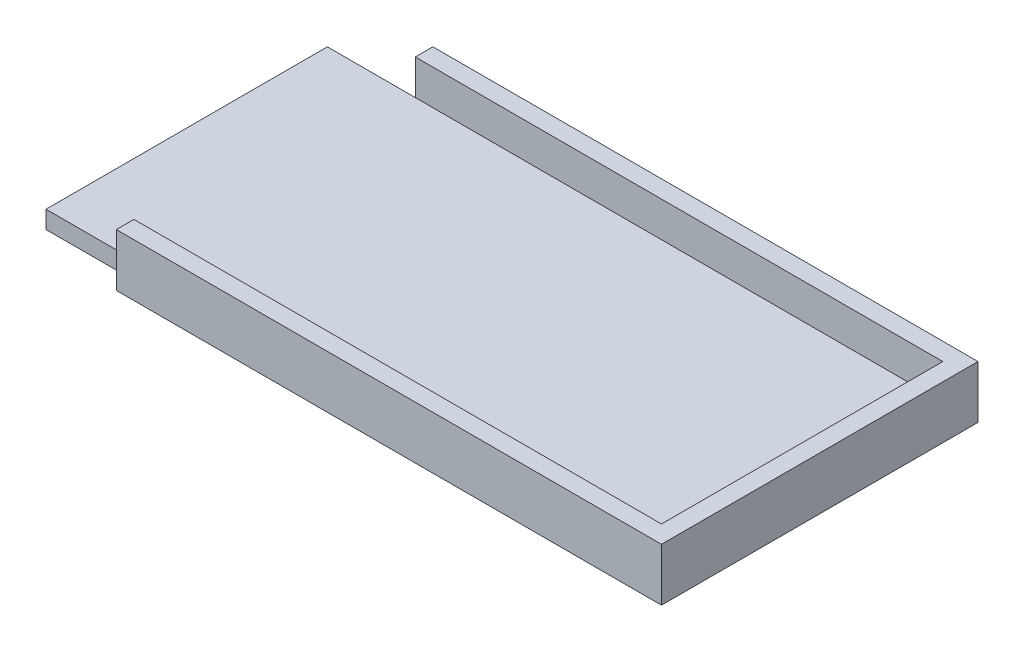
SolidWorks part; units mm, degrees
ref_plane "Front Plane" through (0, 0, 0) normal (0, 0, 1) x (1, 0, 0)
ref_plane "Top Plane" through (0, 0, 0) normal (0, 1, 0) x (1, 0, 0)
ref_plane "Right Plane" through (0, 0, 0) normal (1, 0, 0) x (0, 0, -1)
sketch "Sketch1" plane through (0, 0, 0) normal (0, 1, 0) x (1, 0, 0)
  line L1 (30, -16) -> (-30, -16)
  line L2 (30, -16) -> (30, 16)
  line L3 (30, 16) -> (-30, 16)
  line L4 (-30, -16) -> (-30, 16)
  line L5 (30, -16) -> (-30, 16) construction
  line L6 (30, 16) -> (-30, -16) construction
  point P0 (0, 0)
  dimension "D1" = 60
  dimension "D2" = 32
extrude "Boss-Extrude1" add sketch "Sketch1" along normal blind 2
sketch "Sketch2" plane through (0, 0, 0) normal (0, -1, 0) x (1, 0, 0)
  line L1 (-30, -18) -> (32, -18)
  line L2 (32, -18) -> (32, 18)
  line L3 (32, 18) -> (-30, 18)
  line L4 (-30, 16) -> (-30, -16)
  line L5 (-30, -16) -> (30, -16)
  line L6 (30, -16) -> (30, 16)
  line L7 (30, 16) -> (-30, 16)
  line L9 (-30, -16) -> (30, -16)
  line L10 (30, -16) -> (30, 16)
  line L11 (30, 16) -> (-30, 16)
  line L12 (-32, 18) -> (-32, -18) construction
  line L13 (-30, 16) -> (-30, -16) construction
  line L14 (-30, 16) -> (-30, 18)
  line L15 (-30, -16) -> (-30, -18)
  line L17 (32, 18) -> (-32, 18) construction
  line L18 (-32, -18) -> (32, -18) construction
  dimension "D1" = 0
  dimension "D2" = 2
extrude "Boss-Extrude2" add sketch "Sketch2" along direction (0, -1, 0) on the side against the normal offset from surface (6 mm away) 4
sketch "Sketch3" plane through (0, 0, 0) normal (0, -1, 0) x (1, 0, 0)
  line L0 (-30, -18) -> (-30, 18) construction
  line L1 (-30, -16) -> (-40, -16)
  line L2 (-30, -16) -> (-30, 16)
  line L3 (-30, 16) -> (-40, 16)
  line L4 (-40, -16) -> (-40, 16)
  point P6 (-30, 0)
  point P7 (-30, 0)
  dimension "D1" = 32
  dimension "D2" = 10
extrude "Boss-Extrude3" add sketch "Sketch3" against normal blind 2
